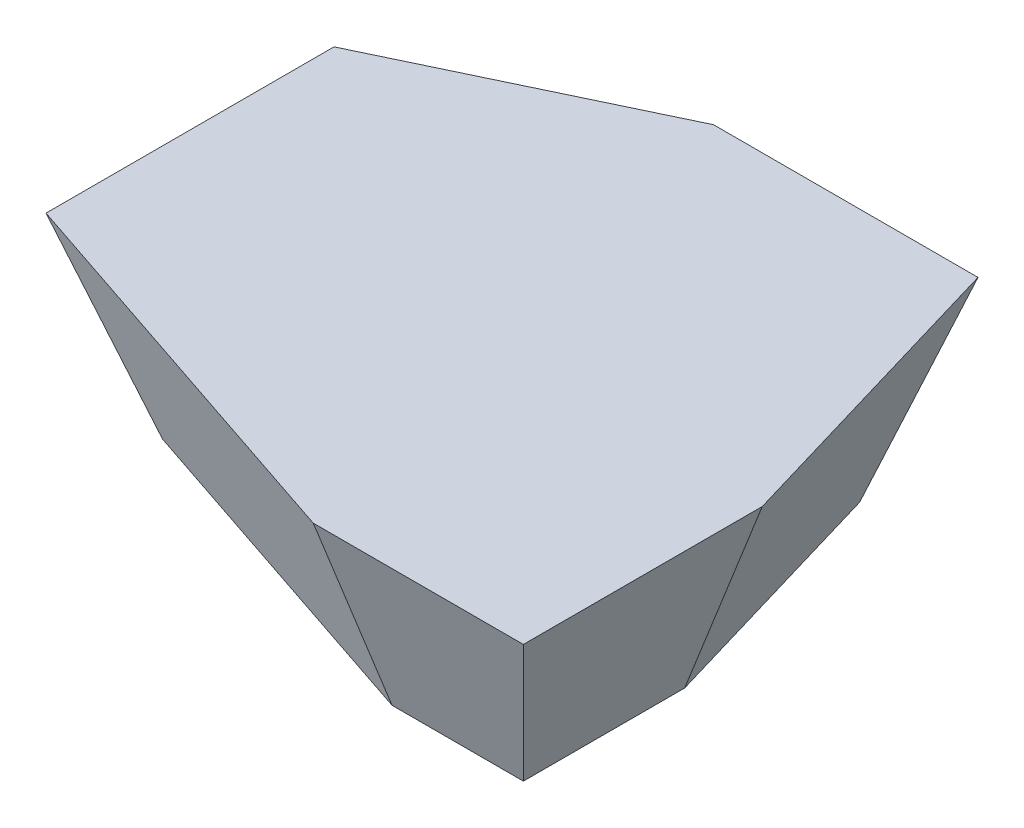
SolidWorks part; units mm, degrees
ref_plane "前视基准面" through (0, 0, 0) normal (0, 0, 1) x (1, 0, 0)
ref_plane "上视基准面" through (0, 0, 0) normal (0, 1, 0) x (1, 0, 0)
ref_plane "右视基准面" through (0, 0, 0) normal (1, 0, 0) x (0, 0, -1)
sketch "草图1" plane through (0, 0, 0) normal (0, 1, 0) x (1, 0, 0)
  line L8 (-61.6405, 14.9936) -> (-61.6405, -11.3841)
  line L9 (-15.2713, -26.933) -> (2.3595, -26.933)
  line L10 (2.3595, -26.933) -> (2.3595, -5.2755)
  line L11 (-7.4968, 28.067) -> (-34.1522, 28.067)
  line L12 (-34.1522, 28.067) -> (-61.6405, 14.9936)
  line L13 (-61.6405, -11.3841) -> (-15.2713, -26.933)
  line L14 (2.3595, -5.2755) -> (-7.4968, 28.067)
  dimension "D1" = 64
  dimension "D2" = 55
extrude "凸台-拉伸1" add sketch "草图1" along normal blind 25
draft "拔模1" type of draft neutral plane draft angle 20 faces to draft 7 face at (-38.4559, 12.5, 19.1585) face at (-61.6405, 12.5, -1.8048) face at (-47.8964, 12.5, -21.5303) face at (-20.8245, 12.5, -28.067) face at (-2.5687, 12.5, -11.3957) face at (2.3595, 12.5, 16.1043) face at (-6.4559, 12.5, 26.933) neutral plane through (0, 0, 0) neutral plane normal (0, -1, 0) parameters "D1"=20
